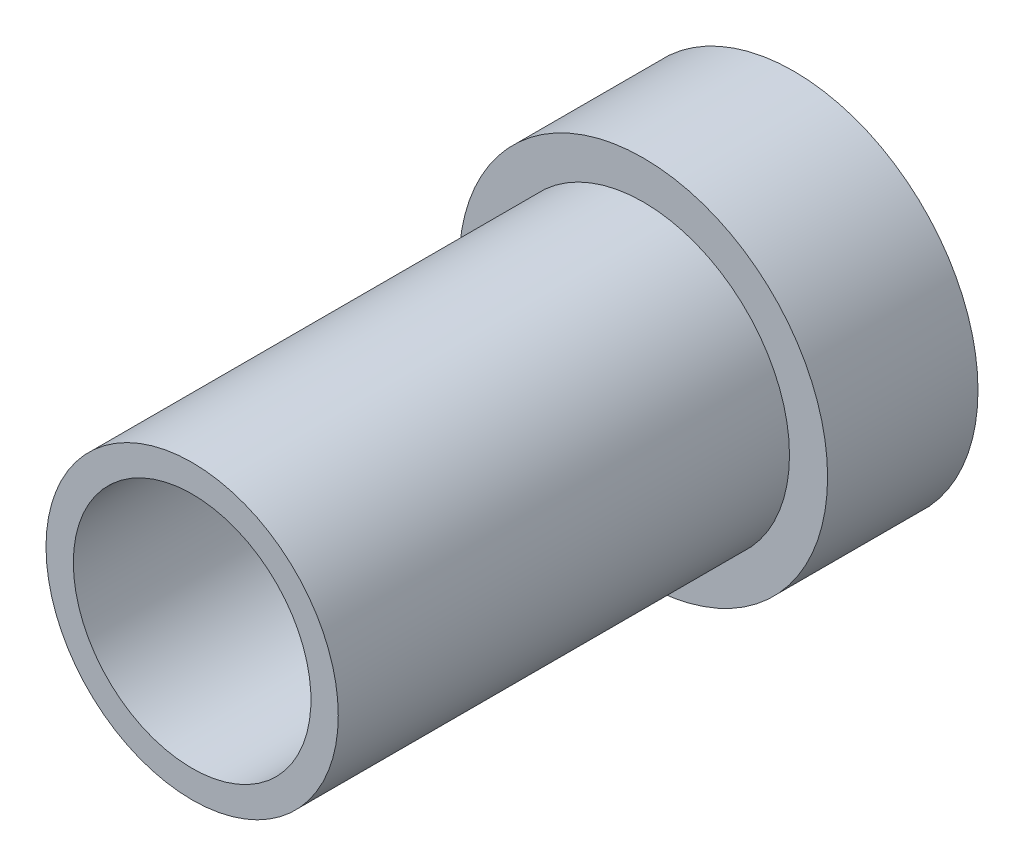
SolidWorks part; units mm, degrees
ref_plane "Plano frontal" through (0, 0, 0) normal (0, 0, 1) x (1, 0, 0)
ref_plane "Plano superior" through (0, 0, 0) normal (0, 1, 0) x (1, 0, 0)
ref_plane "Plano direito" through (0, 0, 0) normal (1, 0, 0) x (0, 0, -1)
ref_plane "Plano1" through (0, 0, 0) normal (0, -1, 0) x (1, 0, 0)
sketch "Esboço1" plane through (0, 0, 0) normal (0, -1, 0) x (1, 0, 0)
  line L0 (18.255, 0) -> (24.5, 0)
  line L1 (24.5, 0) -> (24.5, 20)
  line L2 (24.5, 20) -> (19.4324, 20)
  line L3 (19.4324, 20) -> (19.4324, 80)
  line L4 (19.4324, 80) -> (15.8, 80)
  line L5 (15.8, 80) -> (15.8, 20)
  line L6 (15.8, 20) -> (18.255, 20)
  line L7 (18.255, 20) -> (18.255, 0)
  line L8 (0, 80) -> (0, 0) construction
revolve "Revolução1" add sketch "Esboço1" angle 360 about L8
